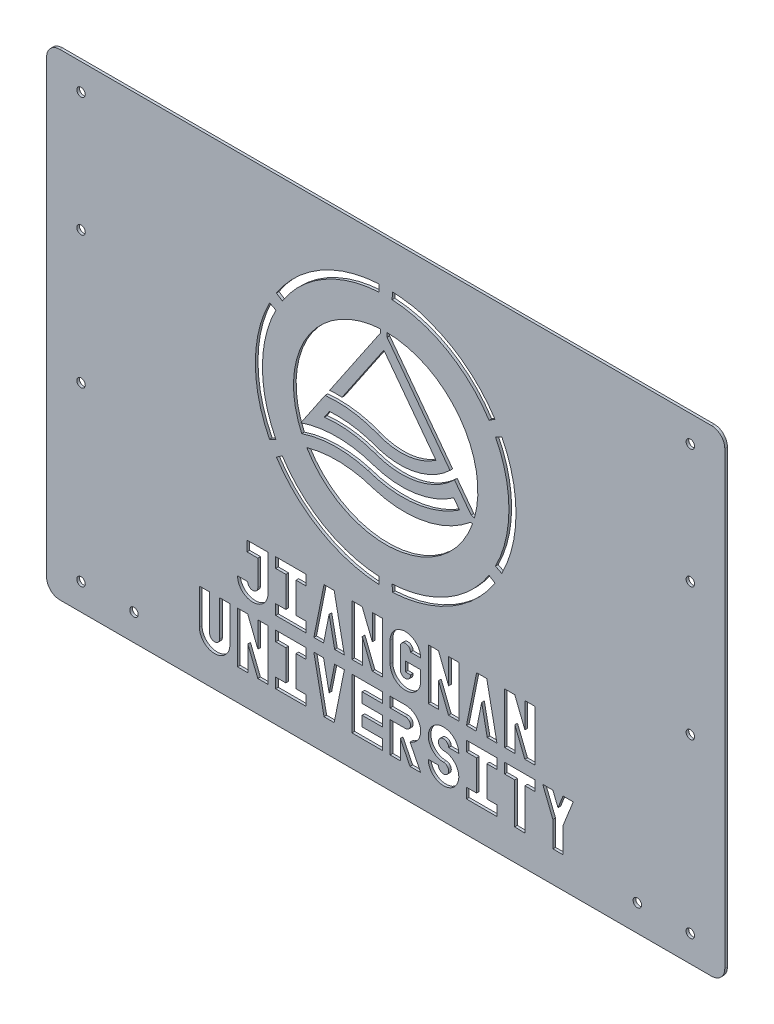
SolidWorks part; units mm, degrees
material "Thornel Mat VMA"
ref_plane "Front Plane" through (0, 0, 0) normal (0, 0, 1) x (1, 0, 0)
ref_plane "Top Plane" through (0, 0, 0) normal (0, 1, 0) x (1, 0, 0)
ref_plane "Right Plane" through (0, 0, 0) normal (1, 0, 0) x (0, 0, -1)
sketch "Model" plane through (0, 0, 0) normal (0, 0, 1) x (1, 0, 0)
  line L0 (128.7882, 150.4427) -> (109.5316, 122.0263)
  line L1 (107.8034, 119.4759) -> (98.619, 105.9228)
  line L2 (129.9882, 145.3684) -> (114.1941, 122.0614)
  line L3 (109.447, 115.0562) -> (107.5438, 112.2478)
  line L4 (131.1882, 150.1642) -> (154.9558, 118.5275)
  line L5 (156.6483, 116.2746) -> (162.94, 107.8999)
  line L6 (129.9882, 145.3684) -> (149.6579, 119.1864)
  line L7 (156.3671, 110.2558) -> (158.5493, 107.3511)
  line L8 (128.7882, 150.4427) -> (128.7882, 151.6851)
  line L9 (131.1882, 150.1642) -> (131.1882, 151.7319)
  line L10 (163.457, 105.2796) -> (162.7488, 105.4693)
  line L11 (164.1823, 107.567) -> (162.94, 107.8999)
  line L12 (78.3472, 57.4211) -> (86.2672, 57.4211)
  line L13 (86.2672, 57.4211) -> (86.2672, 43.9811)
  line L14 (78.3472, 57.4211) -> (78.3472, 53.5811)
  line L15 (78.3472, 53.5811) -> (82.4272, 53.5811)
  line L16 (82.4272, 53.5811) -> (82.4272, 43.9811)
  line L17 (78.5872, 43.9811) -> (74.7472, 43.9811)
  line L18 (129.4672, 57.4211) -> (129.4672, 38.2211)
  line L19 (125.6272, 57.4211) -> (125.6272, 47.8211)
  line L20 (117.9472, 57.4211) -> (117.9472, 38.2211)
  line L21 (121.8236, 47.6368) -> (121.8586, 38.2211)
  line L22 (121.7872, 57.4211) -> (125.6272, 47.8211)
  line L23 (121.8236, 47.6368) -> (125.5898, 38.2211)
  line L24 (129.4672, 38.2211) -> (125.5898, 38.2211)
  line L25 (117.9472, 57.4211) -> (121.7872, 57.4211)
  line L26 (125.6272, 57.4211) -> (129.4672, 57.4211)
  line L27 (117.9472, 38.2211) -> (121.8586, 38.2211)
  line L28 (115.0672, 38.2211) -> (111.3959, 38.2211)
  line L29 (103.5472, 38.2211) -> (107.2184, 38.2211)
  line L30 (103.5472, 38.2211) -> (107.3872, 57.4211)
  line L31 (107.2184, 38.2211) -> (109.3072, 48.6646)
  line L32 (107.3872, 57.4211) -> (111.2272, 57.4211)
  line L33 (111.2272, 57.4211) -> (115.0672, 38.2211)
  line L34 (111.3959, 38.2211) -> (109.3072, 48.6646)
  line L35 (158.2672, 57.4211) -> (158.2672, 38.2211)
  line L36 (154.4272, 57.4211) -> (154.4272, 47.8211)
  line L37 (146.7472, 57.4211) -> (146.7472, 38.2211)
  line L38 (150.6236, 47.6368) -> (150.6586, 38.2211)
  line L39 (150.5872, 57.4211) -> (154.4272, 47.8211)
  line L40 (150.6236, 47.6368) -> (154.3898, 38.2211)
  line L41 (158.2672, 38.2211) -> (154.3898, 38.2211)
  line L42 (146.7472, 57.4211) -> (150.5872, 57.4211)
  line L43 (154.4272, 57.4211) -> (158.2672, 57.4211)
  line L44 (146.7472, 38.2211) -> (150.6586, 38.2211)
  line L45 (117.9472, 33.4211) -> (117.9472, 14.2211)
  line L46 (121.7872, 29.5811) -> (121.7872, 25.7411)
  line L47 (121.7872, 21.9011) -> (121.7872, 18.0611)
  line L48 (121.7872, 33.4211) -> (117.9472, 33.4211)
  line L49 (117.9472, 14.2211) -> (129.4672, 14.2211)
  line L50 (129.4672, 14.2211) -> (129.4672, 18.0611)
  line L51 (129.4672, 18.0611) -> (121.7872, 18.0611)
  line L52 (117.9472, 33.4211) -> (129.4672, 33.4211)
  line L53 (129.4672, 33.4211) -> (129.4672, 29.5811)
  line L54 (129.4672, 29.5811) -> (121.7872, 29.5811)
  line L55 (121.7872, 25.7411) -> (129.4672, 25.7411)
  line L56 (129.4672, 25.7411) -> (129.4672, 21.9011)
  line L57 (129.4672, 21.9011) -> (121.7872, 21.9011)
  line L58 (132.3472, 51.6611) -> (132.3472, 43.9811)
  line L59 (136.1872, 51.6611) -> (136.1872, 43.9811)
  line L60 (140.0272, 51.6611) -> (143.8672, 51.6611)
  line L61 (143.8672, 47.8211) -> (143.8672, 43.9811)
  line L62 (140.0272, 44.2211) -> (138.1072, 44.2211)
  line L63 (138.1072, 44.2211) -> (138.1072, 47.8211)
  line L64 (138.1072, 47.8211) -> (143.8672, 47.8211)
  line L65 (140.0272, 44.2211) -> (140.0272, 43.9811)
  line L66 (187.0672, 57.4211) -> (187.0672, 38.2211)
  line L67 (183.2272, 57.4211) -> (183.2272, 47.8211)
  line L68 (175.5472, 57.4211) -> (175.5472, 38.2211)
  line L69 (179.4236, 47.6368) -> (179.4586, 38.2211)
  line L70 (179.3872, 57.4211) -> (183.2272, 47.8211)
  line L71 (179.4236, 47.6368) -> (183.1898, 38.2211)
  line L72 (187.0672, 38.2211) -> (183.1898, 38.2211)
  line L73 (175.5472, 57.4211) -> (179.3872, 57.4211)
  line L74 (183.2272, 57.4211) -> (187.0672, 57.4211)
  line L75 (175.5472, 38.2211) -> (179.4586, 38.2211)
  line L76 (172.6672, 38.2211) -> (168.9959, 38.2211)
  line L77 (161.1472, 38.2211) -> (164.8184, 38.2211)
  line L78 (161.1472, 38.2211) -> (164.9872, 57.4211)
  line L79 (164.8184, 38.2211) -> (166.9072, 48.6646)
  line L80 (164.9872, 57.4211) -> (168.8272, 57.4211)
  line L81 (168.8272, 57.4211) -> (172.6672, 38.2211)
  line L82 (168.9959, 38.2211) -> (166.9072, 48.6646)
  line L83 (71.8672, 33.4211) -> (71.8672, 19.9811)
  line L84 (68.0272, 33.4211) -> (68.0272, 19.9811)
  line L85 (68.0272, 33.4211) -> (71.8672, 33.4211)
  line L86 (60.3472, 33.4211) -> (60.3472, 19.9811)
  line L87 (64.1872, 33.4211) -> (64.1872, 19.9811)
  line L88 (64.1872, 33.4211) -> (60.3472, 33.4211)
  line L89 (86.2672, 33.4211) -> (86.2672, 14.2211)
  line L90 (82.4272, 33.4211) -> (82.4272, 23.8211)
  line L91 (74.7472, 33.4211) -> (74.7472, 14.2211)
  line L92 (78.6236, 23.6368) -> (78.6586, 14.2211)
  line L93 (78.5872, 33.4211) -> (82.4272, 23.8211)
  line L94 (78.6236, 23.6368) -> (82.3898, 14.2211)
  line L95 (86.2672, 14.2211) -> (82.3898, 14.2211)
  line L96 (74.7472, 33.4211) -> (78.5872, 33.4211)
  line L97 (82.4272, 33.4211) -> (86.2672, 33.4211)
  line L98 (74.7472, 14.2211) -> (78.6586, 14.2211)
  line L99 (89.1472, 57.4211) -> (89.1472, 53.5811)
  line L100 (89.1472, 42.0611) -> (89.1472, 38.2211)
  line L101 (89.1472, 38.2211) -> (100.6672, 38.2211)
  line L102 (100.6672, 38.2211) -> (100.6672, 42.0611)
  line L103 (100.6672, 53.5811) -> (100.6672, 57.4211)
  line L104 (100.6672, 57.4211) -> (89.1472, 57.4211)
  line L105 (89.1472, 53.5811) -> (92.9872, 53.5811)
  line L106 (92.9872, 53.5811) -> (92.9872, 42.0611)
  line L107 (92.9872, 42.0611) -> (89.1472, 42.0611)
  line L108 (100.6672, 53.5811) -> (96.8272, 53.5811)
  line L109 (96.8272, 53.5811) -> (96.8272, 42.0611)
  line L110 (96.8272, 42.0611) -> (100.6672, 42.0611)
  line L111 (89.1472, 33.4211) -> (89.1472, 29.5811)
  line L112 (89.1472, 18.0611) -> (89.1472, 14.2211)
  line L113 (89.1472, 14.2211) -> (100.6672, 14.2211)
  line L114 (100.6672, 14.2211) -> (100.6672, 18.0611)
  line L115 (100.6672, 29.5811) -> (100.6672, 33.4211)
  line L116 (100.6672, 33.4211) -> (89.1472, 33.4211)
  line L117 (89.1472, 29.5811) -> (92.9872, 29.5811)
  line L118 (92.9872, 29.5811) -> (92.9872, 18.0611)
  line L119 (92.9872, 18.0611) -> (89.1472, 18.0611)
  line L120 (100.6672, 29.5811) -> (96.8272, 29.5811)
  line L121 (96.8272, 29.5811) -> (96.8272, 18.0611)
  line L122 (96.8272, 18.0611) -> (100.6672, 18.0611)
  line L123 (103.5472, 33.4211) -> (107.3872, 14.2211)
  line L124 (107.2184, 33.4211) -> (109.3072, 22.9776)
  line L125 (111.2272, 14.2211) -> (115.0672, 33.4211)
  line L126 (109.3072, 22.9776) -> (111.3959, 33.4211)
  line L127 (107.3872, 14.2211) -> (111.2272, 14.2211)
  line L128 (103.5472, 33.4211) -> (107.2184, 33.4211)
  line L129 (115.0672, 33.4211) -> (111.3959, 33.4211)
  line L130 (132.3472, 33.4211) -> (132.3472, 29.5811)
  line L131 (136.1872, 21.5313) -> (136.1872, 14.2211)
  line L132 (132.3472, 14.2211) -> (136.1872, 14.2211)
  line L133 (132.3472, 33.4211) -> (138.1072, 33.4211)
  line L134 (132.3472, 29.5811) -> (138.1072, 29.5811)
  line L135 (139.8863, 22.1828) -> (143.8672, 14.2211)
  line L136 (136.1872, 21.5313) -> (139.8422, 14.2211)
  line L137 (143.8672, 14.2211) -> (139.8422, 14.2211)
  line L138 (132.3472, 25.7411) -> (138.1072, 25.7411)
  line L139 (146.7472, 19.9811) -> (150.5872, 19.9811)
  line L140 (154.4272, 27.6611) -> (158.2672, 27.6611)
  line L141 (161.1472, 33.4211) -> (161.1472, 29.5811)
  line L142 (161.1472, 18.0611) -> (161.1472, 14.2211)
  line L143 (161.1472, 14.2211) -> (172.6672, 14.2211)
  line L144 (172.6672, 14.2211) -> (172.6672, 18.0611)
  line L145 (172.6672, 29.5811) -> (172.6672, 33.4211)
  line L146 (172.6672, 33.4211) -> (161.1472, 33.4211)
  line L147 (161.1472, 29.5811) -> (164.9872, 29.5811)
  line L148 (164.9872, 29.5811) -> (164.9872, 18.0611)
  line L149 (164.9872, 18.0611) -> (161.1472, 18.0611)
  line L150 (172.6672, 29.5811) -> (168.8272, 29.5811)
  line L151 (168.8272, 29.5811) -> (168.8272, 18.0611)
  line L152 (168.8272, 18.0611) -> (172.6672, 18.0611)
  line L153 (175.5472, 33.4211) -> (175.5472, 29.5811)
  line L154 (187.0672, 29.5811) -> (187.0672, 33.4211)
  line L155 (187.0672, 33.4211) -> (175.5472, 33.4211)
  line L156 (175.5472, 29.5811) -> (179.3872, 29.5811)
  line L157 (179.3872, 29.5811) -> (179.3872, 14.2211)
  line L158 (187.0672, 29.5811) -> (183.2272, 29.5811)
  line L159 (183.2272, 29.5811) -> (183.2272, 14.0876)
  line L160 (179.3872, 14.2211) -> (183.2272, 14.0876)
  line L161 (193.7872, 23.8211) -> (193.8222, 14.2211)
  line L162 (193.7872, 33.4211) -> (195.7072, 28.6211)
  line L163 (189.9472, 33.4211) -> (193.7872, 33.4211)
  line L164 (197.6272, 33.4211) -> (201.4672, 33.4211)
  line L165 (197.6272, 33.4211) -> (195.7072, 28.6211)
  line L166 (189.9472, 33.4211) -> (193.7872, 23.8211)
  line L167 (201.4672, 33.4211) -> (197.6272, 23.8211)
  line L168 (197.6272, 23.8211) -> (197.5921, 14.2211)
  line L169 (193.8222, 14.2211) -> (197.5921, 14.2211)
  line L170 (7.6672, 182.5384) -> (253.6672, 182.5384)
  line L171 (2.6672, 177.5384) -> (2.6672, 7.5384)
  line L172 (7.6672, 2.5384) -> (253.6672, 2.5384)
  line L173 (258.6672, 7.5384) -> (258.6672, 177.5384)
  line L174 (128.2319, 163.4027) -> (128.0922, 166.0684)
  line L175 (133.1024, 163.4027) -> (133.2421, 166.0684)
  line L176 (89.2081, 138.0603) -> (86.8296, 139.2722)
  line L177 (91.6433, 142.2782) -> (89.4046, 143.7321)
  line L178 (172.1262, 138.0603) -> (174.5047, 139.2722)
  line L179 (169.691, 142.2782) -> (171.9297, 143.7321)
  line L180 (128.2319, 70.469) -> (128.0922, 67.8033)
  line L181 (133.1024, 70.469) -> (133.2421, 67.8033)
  line L182 (89.2081, 95.8114) -> (86.8296, 94.5995)
  line L183 (91.6433, 91.5935) -> (89.4046, 90.1396)
  line L184 (172.1262, 95.8114) -> (174.5047, 94.5995)
  line L185 (169.691, 91.5935) -> (171.9297, 90.1396)
  line L186 (132.3472, 25.7411) -> (132.3472, 14.2211)
  arc A0 (128.0922, 166.0684) -> (89.4046, 143.7321) centre (130.6672, 116.9358) ccw
  arc A1 (86.8296, 139.2722) -> (86.8296, 94.5995) centre (130.6672, 116.9358) ccw
  arc A2 (89.4046, 90.1396) -> (128.0922, 67.8033) centre (130.6672, 116.9358) ccw
  arc A3 (133.2421, 67.8033) -> (171.9297, 90.1396) centre (130.6672, 116.9358) ccw
  arc A4 (174.5047, 94.5995) -> (174.5047, 139.2722) centre (130.6672, 116.9358) ccw
  arc A5 (171.9297, 143.7321) -> (133.2421, 166.0684) centre (130.6672, 116.9358) ccw
  arc A6 (100.8746, 98.9514) -> (163.457, 105.2796) centre (130.6672, 116.9358) ccw
  arc A7 (164.1823, 107.567) -> (131.1882, 151.7319) centre (130.6672, 116.9358) ccw
  arc A8 (128.7882, 151.6851) -> (98.971, 102.5695) centre (130.6672, 116.9358) ccw
  arc A9 (125.9827, 105.8594) -> (98.6262, 105.9335) centre (112.197, 66.1863) ccw
  arc A10 (126.1209, 102.3312) -> (98.971, 102.5695) centre (112.197, 62.7063) ccw
  arc A11 (126.1493, 98.1212) -> (100.8746, 98.9514) centre (112.197, 58.5063) ccw
  arc A12 (126.8225, 109.8776) -> (107.5438, 112.2478) centre (112.197, 70.5063) ccw
  arc A13 (127.6949, 112.1824) -> (109.447, 115.0562) centre (112.197, 73.1463) ccw
  arc A14 (128.0487, 116.6001) -> (107.8034, 119.4759) centre (112.197, 77.7063) ccw
  arc A15 (114.1941, 122.0614) -> (109.5316, 122.0263) centre (112.197, 77.7063) ccw
  arc A16 (124.6903, 98.6052) -> (162.7488, 105.4693) centre (137.704, 135.3909) ccw
  arc A17 (123.9056, 103.0413) -> (158.5493, 107.3511) centre (136.9193, 139.827) ccw
  arc A18 (125.595, 105.9921) -> (156.3671, 110.2558) centre (136.8176, 138.1715) ccw
  arc A19 (126.69, 109.9266) -> (156.6483, 116.2746) centre (136.6654, 136.7152) ccw
  arc A20 (147.5254, 163.1575) -> (142.3216, 164.7356) centre (136.6654, 136.7152) ccw
  arc A21 (125.527, 112.9749) -> (154.9558, 118.5275) centre (135.9958, 138.2528) ccw
  arc A22 (146.4646, 163.5307) -> (138.6528, 165.4834) centre (135.9958, 138.2528) ccw
  arc A23 (127.5099, 116.8154) -> (149.6579, 119.1864) centre (136.4098, 138.3094) ccw
  arc A24 (128.2319, 163.4027) -> (91.6433, 142.2782) centre (130.6672, 116.9358) ccw
  arc A25 (89.2081, 138.0603) -> (89.2081, 95.8114) centre (130.6672, 116.9358) ccw
  arc A26 (91.6433, 91.5935) -> (128.2319, 70.469) centre (130.6672, 116.9358) ccw
  arc A27 (133.1024, 70.469) -> (169.691, 91.5935) centre (130.6672, 116.9358) ccw
  arc A28 (172.1262, 95.8114) -> (172.1262, 138.0603) centre (130.6672, 116.9358) ccw
  arc A29 (169.691, 142.2782) -> (133.1024, 163.4027) centre (130.6672, 116.9358) ccw
  arc A30 (74.7472, 43.9811) -> (86.2672, 43.9811) centre (80.5072, 43.9811) ccw
  arc A31 (78.5872, 43.9811) -> (82.4272, 43.9811) centre (80.5072, 43.9811) ccw
  arc A32 (132.3472, 43.9811) -> (143.8672, 43.9811) centre (138.1072, 43.9811) ccw
  arc A33 (136.1872, 43.9811) -> (140.0272, 43.9811) centre (138.1072, 43.9811) ccw
  arc A34 (143.8672, 51.6611) -> (132.3472, 51.6611) centre (138.1072, 51.6611) ccw
  arc A35 (140.0272, 51.6611) -> (136.1872, 51.6611) centre (138.1072, 51.6611) ccw
  arc A36 (60.3472, 19.9811) -> (71.8672, 19.9811) centre (66.1072, 19.9811) ccw
  arc A37 (64.1872, 19.9811) -> (68.0272, 19.9811) centre (66.1072, 19.9811) ccw
  arc A38 (143.8672, 27.6611) -> (138.1072, 33.4211) centre (138.1072, 27.6611) ccw
  arc A39 (140.0272, 27.6611) -> (138.1072, 29.5811) centre (138.1072, 27.6611) ccw
  arc A40 (139.8863, 22.1828) -> (143.8672, 27.6611) centre (138.1072, 27.6611) ccw
  arc A41 (138.1072, 25.7411) -> (140.0272, 27.6611) centre (138.1072, 27.6611) ccw
  arc A42 (146.7472, 19.9811) -> (158.2672, 19.9811) centre (152.5072, 19.9811) ccw
  arc A43 (150.5872, 19.9811) -> (154.4272, 19.9811) centre (152.5072, 19.9811) ccw
  arc A44 (158.2672, 27.6611) -> (146.7472, 27.6611) centre (152.5072, 27.6611) ccw
  arc A45 (154.4272, 27.6611) -> (150.5872, 27.6611) centre (152.5072, 27.6611) ccw
  arc A46 (146.7472, 27.6611) -> (152.5072, 21.9011) centre (152.5072, 27.6611) ccw
  arc A47 (150.5872, 27.6611) -> (152.5072, 25.7411) centre (152.5072, 27.6611) ccw
  arc A48 (158.2672, 19.9811) -> (152.5072, 25.7411) centre (152.5072, 19.9811) ccw
  arc A49 (154.4272, 19.9811) -> (152.5072, 21.9011) centre (152.5072, 19.9811) ccw
  circle A50 centre (15.6672, 172.5384) radius 1.6
  circle A51 centre (15.6672, 127.5384) radius 1.6
  circle A52 centre (15.6672, 77.5384) radius 1.6
  circle A53 centre (245.6672, 172.5384) radius 1.6
  circle A54 centre (245.6672, 127.5384) radius 1.6
  circle A55 centre (245.6672, 77.5384) radius 1.6
  arc A56 (258.6672, 177.5384) -> (253.6672, 182.5384) centre (253.6672, 177.5384) ccw
  arc A57 (7.6672, 182.5384) -> (2.6672, 177.5384) centre (7.6672, 177.5384) ccw
  arc A58 (2.6672, 7.5384) -> (7.6672, 2.5384) centre (7.6672, 7.5384) ccw
  arc A59 (253.6672, 2.5384) -> (258.6672, 7.5384) centre (253.6672, 7.5384) ccw
  circle A60 centre (15.6672, 12.5384) radius 1.6
  circle A61 centre (245.6672, 12.5384) radius 1.6
  circle A62 centre (35.6672, 12.5384) radius 1.6
  circle A63 centre (225.6672, 12.5384) radius 1.6
extrude "Boss-Extrude1" add sketch "Model" along normal blind 1 contours L172 A59 L173 A56 L170 A57 L171 A58 A63 A62 A61 A60 A43 A49 A46 A44 L140 A45 A47 A48 A42 L139 L138 A41 A39 L134 L130 L133 A38 A40 L135 L137 L136 L131 L132 L186 L87 A37 L84 L85 L83 A36 L86 L88
